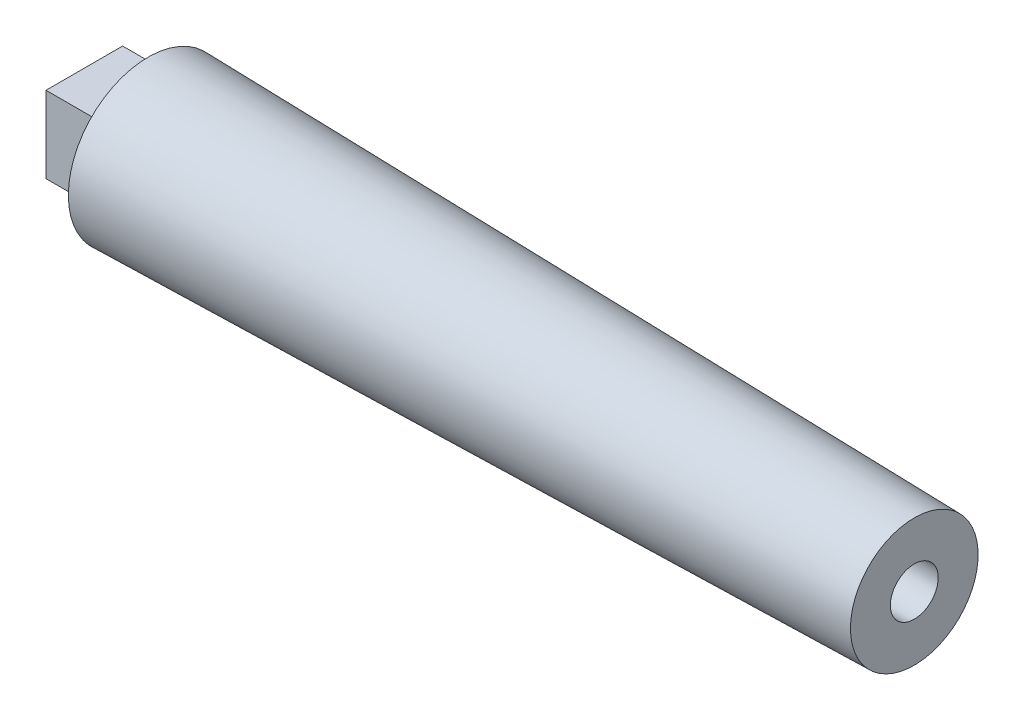
SolidWorks part; units mm, degrees
ref_plane "Front Plane" through (0, 0, 0) normal (0, 0, 1) x (1, 0, 0)
ref_plane "Top Plane" through (0, 0, 0) normal (0, 1, 0) x (1, 0, 0)
ref_plane "Right Plane" through (0, 0, 0) normal (1, 0, 0) x (0, 0, -1)
sketch "Sketch1" plane through (0, 0, 0) normal (0, 0, 1) x (1, 0, 0)
  line L0 (0, 0) -> (208.7573, 0) construction
  line L1 (0, 0) -> (152.4, 0)
  line L2 (152.4, 0) -> (152.4, 12.7)
  line L5 (0, 15.875) -> (0, 0)
  line L6 (0, 15.875) -> (152.4, 12.7)
  dimension "D1" = 152.4
  dimension "D2" = 31.75
  dimension "D3" = 25.4
revolve "Revolve2" add sketch "Sketch1" angle 360 about L0
sketch "Sketch3" plane through (152.4, 0, 0) normal (1, 0, 0) x (0, 0, -1)
  circle A0 centre (0, 0) radius 4.7625
  point P0 (0, 0)
  dimension "D1" = 9.525
extrude "Cut-Extrude1" cut sketch "Sketch3" against normal blind 25.4 contours A0
sketch "Sketch4" plane through (0, 0, 0) normal (-1, 0, 0) x (0, 0, 1)
  line L1 (-7.62, 7.62) -> (7.62, 7.62)
  line L2 (-7.62, 7.62) -> (-7.62, -7.62)
  line L3 (-7.62, -7.62) -> (7.62, -7.62)
  line L4 (7.62, 7.62) -> (7.62, -7.62)
  line L5 (-7.62, 7.62) -> (7.62, -7.62) construction
  line L6 (-7.62, -7.62) -> (7.62, 7.62) construction
  point P0 (0, 0)
  dimension "D1" = 15.24
  dimension "D2" = 15.24
extrude "Boss-Extrude1" add sketch "Sketch4" along normal blind 12.7
